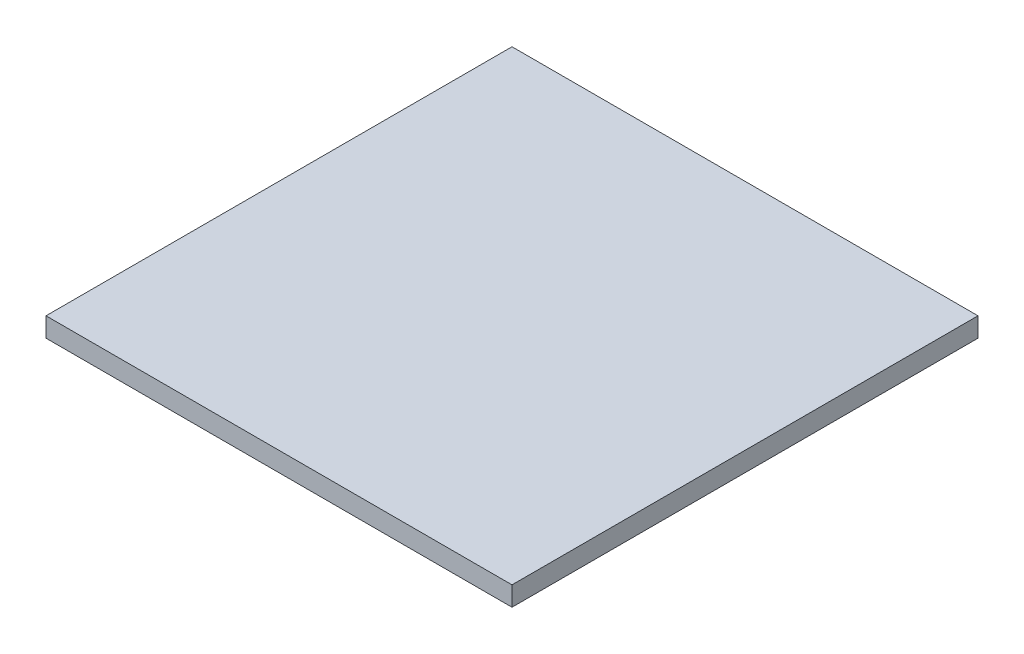
SolidWorks part; units mm, degrees
ref_plane "Front Plane" through (0, 0, 0) normal (0, 0, 1) x (1, 0, 0)
ref_plane "Top Plane" through (0, 0, 0) normal (0, 1, 0) x (1, 0, 0)
ref_plane "Right Plane" through (0, 0, 0) normal (1, 0, 0) x (0, 0, -1)
sketch "Sketch1" plane through (0, 0, 0) normal (0, 1, 0) x (1, 0, 0)
  line L1 (-252.4204, 29.4152) -> (52.3796, 29.4152)
  line L2 (-252.4204, 29.4152) -> (-252.4204, -275.3848)
  line L3 (-252.4204, -275.3848) -> (52.3796, -275.3848)
  line L4 (52.3796, 29.4152) -> (52.3796, -275.3848)
  dimension "D1" = 304.8
  dimension "D2" = 304.8
extrude "Boss-Extrude1" add sketch "Sketch1" along normal blind 12.7 contours L2 L3 L4 L1
